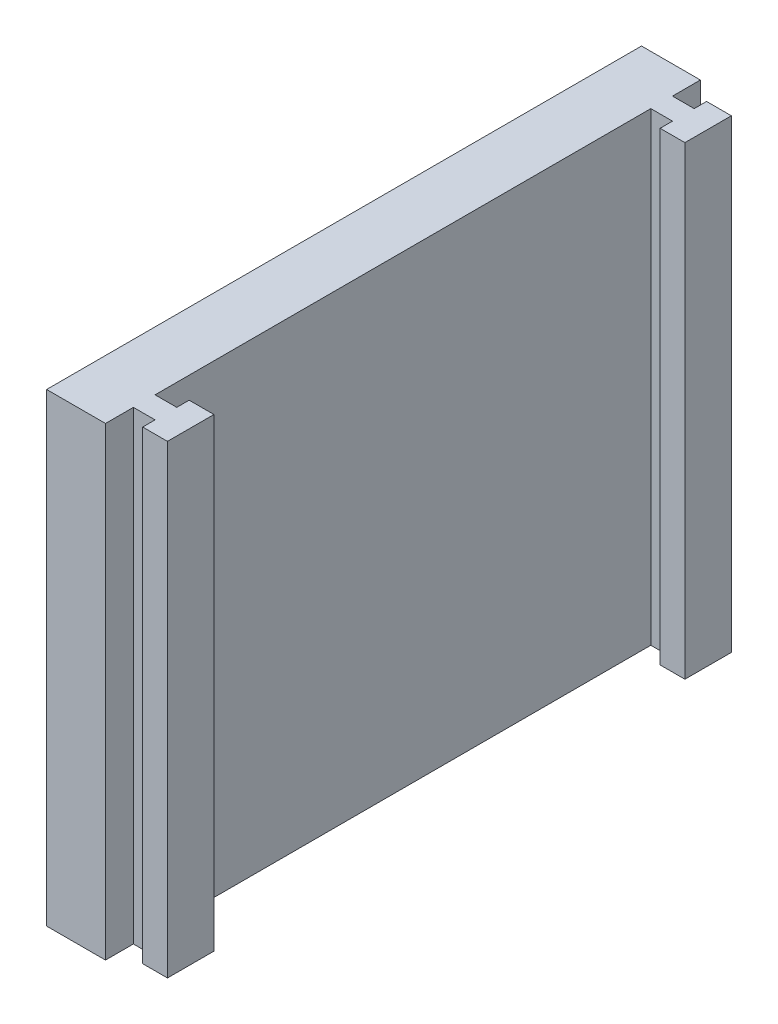
SolidWorks part; units mm, degrees
ref_plane "Piano frontale" through (0, 0, 0) normal (0, 0, 1) x (1, 0, 0)
ref_plane "Piano superiore" through (0, 0, 0) normal (0, 1, 0) x (1, 0, 0)
ref_plane "Piano destro" through (0, 0, 0) normal (1, 0, 0) x (0, 0, -1)
sketch "Schizzo2" plane through (0, 0, 0) normal (0, 1, 0) x (1, 0, 0)
  line L0 (19, 96) -> (19, 87)
  line L5 (19, 87) -> (26, 87)
  line L6 (19, 0) -> (0, 0)
  line L8 (19, 96) -> (0, 96)
  line L9 (0, 0) -> (0, 96)
  line L10 (26, 87) -> (26, 91)
  line L11 (26, 91) -> (34, 91)
  line L12 (26, 76) -> (26, 80)
  line L13 (34, 91) -> (34, 76)
  line L14 (26, 80) -> (19, 80)
  line L15 (19, 80) -> (19, 0)
  line L21 (34, 76) -> (26, 76)
  point P21 (34, 83.5)
  dimension "D1" = 7
  dimension "D2" = 8
  dimension "D3" = 34
  dimension "D4" = 19
  dimension "D5" = 0
  dimension "D6" = 0
  dimension "D7" = 15
  dimension "D8" = 12.5
  dimension "D9" = 5
  dimension "D10" = 4
  dimension "D11" = 4
  dimension "D12" = 9
  dimension "D13" = 96
  dimension "D15" = 80
extrude "Estrusione-Estrusione1" add sketch "Schizzo2" along normal blind 150
sketch "Schizzo3" plane through (0, 0, 0) normal (0, -1, 0) x (1, 0, 0)
  line L3 (8.958, -91) -> (5, -91)
  line L4 (8.958, -74) -> (5, -74)
  line L5 (5, -91) -> (5, -74)
  line L6 (0, -96) -> (0, 0) construction
  line L8 (19, -96) -> (0, -96) construction
  arc A0 (8.958, -74) -> (8.958, -91) centre (6, -82.5) cw
  point P6 (15, -82.5)
  point P12 (-13.0687, -70.0502)
  dimension "D3" = 17
  dimension "D5" = 9
  dimension "D1" = 5
  dimension "D2" = 5
  dimension "D4" = 10
  dimension "D6" = 3.958
extrude "Taglio-Estrusione1" cut sketch "Schizzo3" against normal blind 145
mirror "Specchia2" about plane through (19, 150, 0) normal (0, 0, -1) of bodies 103
